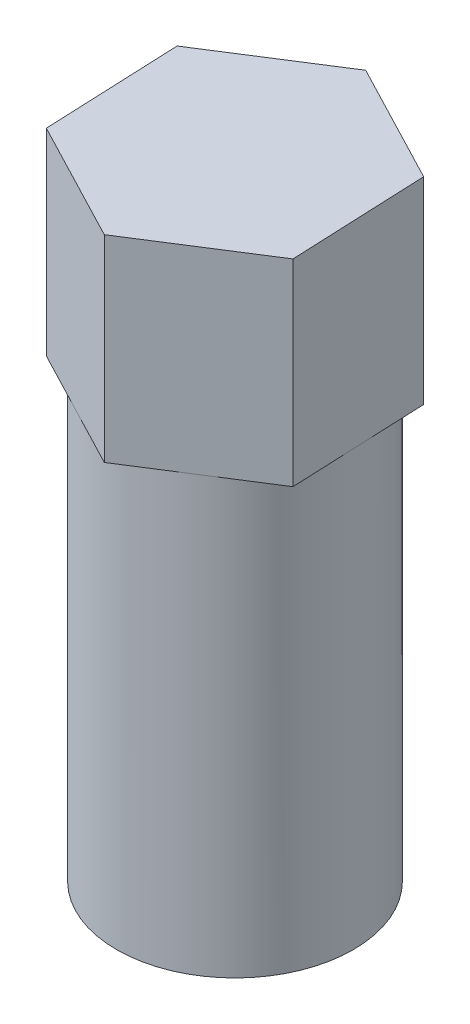
SolidWorks part; units mm, degrees
ref_plane "Front Plane" through (0, 0, 0) normal (0, 0, 1) x (1, 0, 0)
ref_plane "Top Plane" through (0, 0, 0) normal (0, 1, 0) x (1, 0, 0)
ref_plane "Right Plane" through (0, 0, 0) normal (1, 0, 0) x (0, 0, -1)
sketch "Sketch1" plane through (0, 0, 0) normal (0, 1, 0) x (1, 0, 0)
  line L1 (6.1424, -3.2048) -> (5.8466, 3.7171)
  line L2 (5.8466, 3.7171) -> (-0.2958, 6.9219)
  line L3 (-0.2958, 6.9219) -> (-6.1424, 3.2048)
  line L4 (-6.1424, 3.2048) -> (-5.8466, -3.7171)
  line L5 (-5.8466, -3.7171) -> (0.2958, -6.9219)
  line L6 (0.2958, -6.9219) -> (6.1424, -3.2048)
  circle A0 centre (0, 0) radius 6 construction
  dimension "D1" = 12
extrude "Boss-Extrude1" add sketch "Sketch1" along normal blind 10
sketch "Sketch6" plane through (0, 0, 0) normal (0, -1, 0) x (1, 0, 0)
  circle A0 centre (0, 0) radius 6
extrude "Boss-Extrude2" add sketch "Sketch6" along normal blind 22
